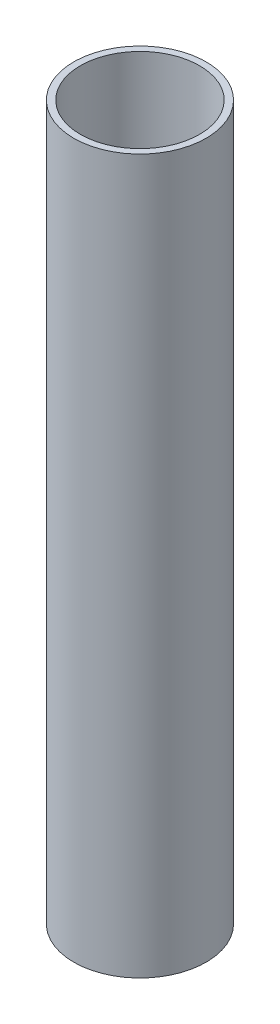
SolidWorks part; units mm, degrees
ref_plane "Front Plane" through (0, 0, 0) normal (0, 0, 1) x (1, 0, 0)
ref_plane "Top Plane" through (0, 0, 0) normal (0, 1, 0) x (1, 0, 0)
ref_plane "Right Plane" through (0, 0, 0) normal (1, 0, 0) x (0, 0, -1)
sketch "Sketch1" plane through (0, 0, 0) normal (0, 1, 0) x (1, 0, 0)
  circle A0 centre (0, 0) radius 10
  circle A1 centre (0, 0) radius 9
extrude "Boss-Extrude1" add sketch "Sketch1" along normal blind 107.8
